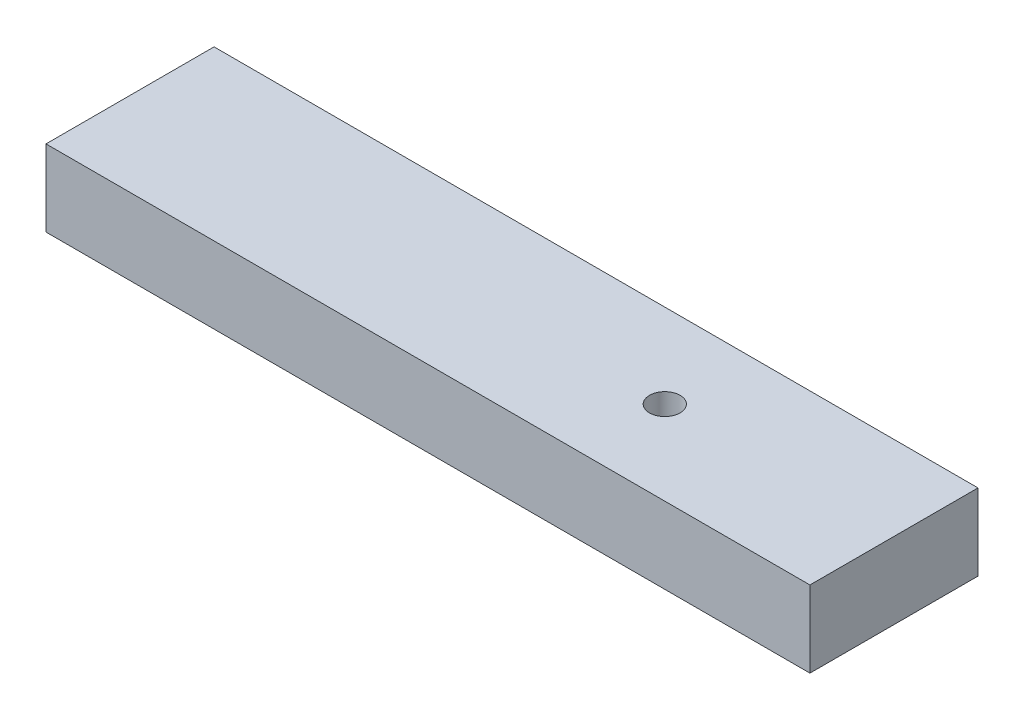
SolidWorks part; units mm, degrees
ref_plane "Front Plane" through (0, 0, 0) normal (0, 0, 1) x (1, 0, 0)
ref_plane "Top Plane" through (0, 0, 0) normal (0, 1, 0) x (1, 0, 0)
ref_plane "Right Plane" through (0, 0, 0) normal (1, 0, 0) x (0, 0, -1)
sketch "Sketch1" plane through (0, 0, 0) normal (0, 1, 0) x (1, 0, 0)
  line L1 (-125, 27.5) -> (125, 27.5)
  line L2 (-125, 27.5) -> (-125, -27.5)
  line L3 (-125, -27.5) -> (125, -27.5)
  line L4 (125, 27.5) -> (125, -27.5)
  line L5 (-125, 27.5) -> (125, -27.5) construction
  line L6 (-125, -27.5) -> (125, 27.5) construction
  point P0 (0, 0)
  dimension "D1" = 250
  dimension "D2" = 55
extrude "Boss-Extrude1" add sketch "Sketch1" along normal blind 25
sketch "Sketch2" plane through (0, 25, 0) normal (0, 1, 0) x (1, 0, 0)
  line L0 (125, -27.5) -> (125, 27.5) construction
  circle A0 centre (50, 0) radius 5
  point P2 (0, 0)
  dimension "D1" = 10
  dimension "D2" = 75
extrude "Cut-Extrude1" cut sketch "Sketch2" against normal through all
